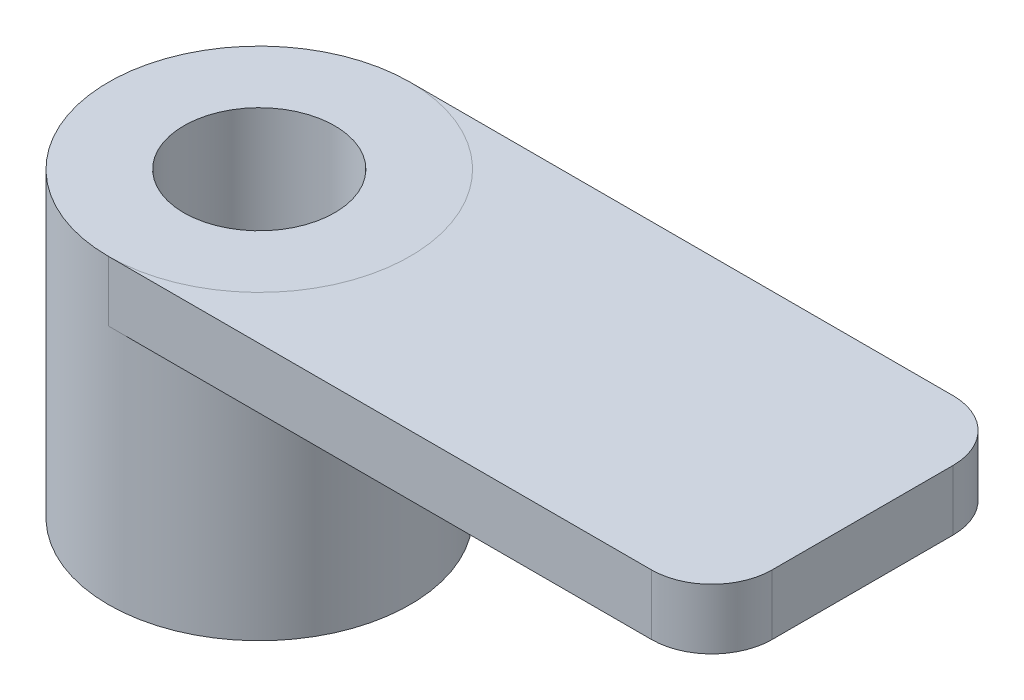
SolidWorks part; units mm, degrees
ref_plane "Front Plane" through (0, 0, 0) normal (0, 0, 1) x (1, 0, 0)
ref_plane "Top Plane" through (0, 0, 0) normal (0, 1, 0) x (1, 0, 0)
ref_plane "Right Plane" through (0, 0, 0) normal (1, 0, 0) x (0, 0, -1)
sketch "Sketch1" plane through (0, 0, 0) normal (0, 1, 0) x (1, 0, 0)
  circle A0 centre (0, 0) radius 3.175
  circle A1 centre (0, 0) radius 6.35
  dimension "D1" = 6.35
  dimension "D2" = 12.7
extrude "Boss-Extrude1" add sketch "Sketch1" along normal blind 12.7
sketch "Sketch2" plane through (0, 12.7, 0) normal (0, 1, 0) x (1, 0, 0)
  line L0 (0, 6.35) -> (25.4, 6.35)
  line L1 (25.4, 6.35) -> (25.4, -6.35)
  line L2 (25.4, -6.35) -> (0, -6.35)
  circle A0 centre (0, 0) radius 6.35 construction
  arc A2 (0, -6.35) -> (0, 6.35) centre (0, 0) ccw
  dimension "D1" = 25.4
extrude "Boss-Extrude2" add sketch "Sketch2" against normal blind 2.54 separate body
fillet "Fillet1" radius 2.54 2 edges at (25.4, 11.43, 6.35) (25.4, 11.43, -6.35)
